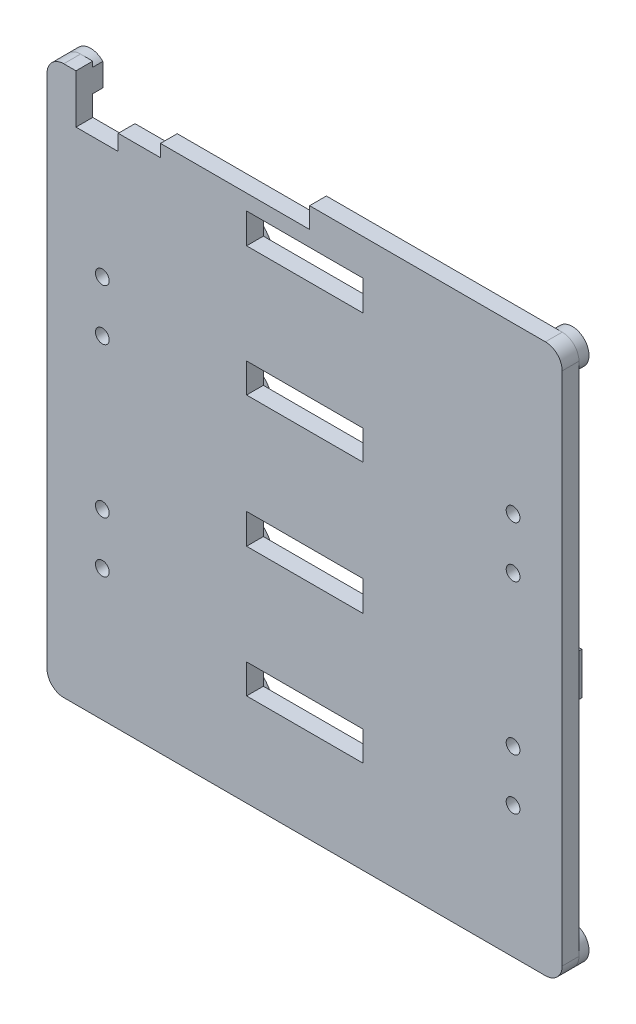
SolidWorks part; units mm, degrees
ref_plane "前视基准面" through (0, 0, 0) normal (0, 0, 1) x (1, 0, 0)
ref_plane "上视基准面" through (0, 0, 0) normal (0, 1, 0) x (1, 0, 0)
ref_plane "右视基准面" through (0, 0, 0) normal (1, 0, 0) x (0, 0, -1)
other "Configuration Table"
ref_plane "基准面1" through (0, 0, -42.5914) normal (0, 0, -1) x (-1, 0, 0)
sketch "草图1" plane through (0, 0, -42.5914) normal (0, 0, -1) x (-1, 0, 0)
  line L20 (41.4092, 120.2374) -> (-102.2385, 120.2373)
  line L21 (-107.2387, 115.2372) -> (-107.2386, -38.4842)
  line L22 (-102.2402, -43.4827) -> (41.4109, -43.4826)
  line L23 (46.4094, -38.4842) -> (46.4093, 115.2372)
  arc A20 (46.4093, 115.2372) -> (41.4092, 120.2374) centre (41.4092, 115.2372) ccw
  arc A21 (-102.2385, 120.2373) -> (-107.2387, 115.2372) centre (-102.2385, 115.2372) ccw
  arc A22 (-107.2386, -38.4842) -> (-102.2402, -43.4827) centre (-102.2402, -38.4842) ccw
  arc A23 (41.4109, -43.4826) -> (46.4094, -38.4842) centre (41.4109, -38.4842) ccw
extrude "凸台-拉伸1" add sketch "草图1" along normal blind 5
sketch "草图3" plane through (0, 0, -47.5914) normal (0, 0, -1) x (-1, 0, 0)
  line L5 (22.0323, 45.3277) -> (11.4184, 45.3277)
  line L6 (22.0323, 45.3277) -> (22.0323, 20.4419)
  line L7 (22.0323, 20.4419) -> (11.4184, 20.4419)
  line L8 (11.4184, 45.3277) -> (11.4184, 20.4419)
  line L9 (-66.1205, 38.2743) -> (-105.0787, 38.2743)
  line L10 (-66.1205, 38.2743) -> (-66.1205, 25.6801)
  line L11 (-66.1205, 25.6801) -> (-105.0787, 25.6801)
  line L12 (-105.0787, 38.2743) -> (-105.0787, 25.6801)
  line L13 (-76.2404, 116.5516) -> (-89.8192, 116.5516)
  line L14 (-76.2404, 116.5516) -> (-76.2404, 82.3988)
  line L15 (-76.2404, 82.3988) -> (-89.8192, 82.3988)
  line L16 (-89.8192, 116.5516) -> (-89.8192, 82.3988)
  line L17 (26.5757, 102.6562) -> (14.4763, 102.6562)
  line L18 (26.5757, 102.6562) -> (26.5757, 79.5664)
  line L19 (26.5757, 79.5664) -> (14.4763, 79.5664)
  line L20 (14.4763, 102.6562) -> (14.4763, 79.5664)
  line L21 (24.3318, -15.6667) -> (16.7254, -15.6667)
  line L22 (24.3318, -15.6667) -> (24.3318, -38.483)
  line L23 (24.3318, -38.483) -> (16.7254, -38.483)
  line L24 (16.7254, -15.6667) -> (16.7254, -38.483)
  line L25 (-76.2404, -15.6667) -> (-87.4137, -15.6667)
  line L26 (-76.2404, -15.6667) -> (-76.2404, -38.483)
  line L27 (-76.2404, -38.483) -> (-87.4137, -38.483)
  line L28 (-87.4137, -15.6667) -> (-87.4137, -38.483)
  circle A0 centre (-3.5966, 93.0119) radius 6.625 construction
  circle A1 centre (-3.581, 54.2036) radius 6.625 construction
  circle A2 centre (-59.0858, 90.0418) radius 6.625 construction
  circle A3 centre (-59.0702, 51.2335) radius 6.625 construction
  circle A4 centre (-59.039, -26.383) radius 6.625 construction
  circle A5 centre (-59.0546, 12.4253) radius 6.625 construction
  circle A6 centre (-3.5654, 15.3953) radius 6.625 construction
  circle A7 centre (-3.5498, -23.413) radius 6.625 construction
  circle A8 centre (-3.5966, 93.0119) radius 6.625 construction
  circle A9 centre (-3.581, 54.2036) radius 6.625 construction
  circle A10 centre (-59.0858, 90.0418) radius 6.625 construction
  circle A11 centre (-59.0702, 51.2335) radius 6.625 construction
  circle A12 centre (-59.039, -26.383) radius 6.625 construction
  circle A13 centre (-59.0546, 12.4253) radius 6.625 construction
  circle A14 centre (-3.5654, 15.3953) radius 6.625 construction
  circle A15 centre (-3.5498, -23.413) radius 6.625 construction
  circle A16 centre (41.4105, 115.237) radius 5
  circle A17 centre (41.4105, 115.237) radius 5
  circle A20 centre (-102.2375, 115.237) radius 2
  circle A21 centre (41.4105, 115.237) radius 2
  circle A22 centre (-102.2375, 115.237) radius 5
  circle A23 centre (-102.2375, 115.237) radius 5
  circle A24 centre (-102.2375, -38.483) radius 5
  circle A25 centre (-102.2375, -38.483) radius 5
  circle A26 centre (41.4105, -38.483) radius 5
  circle A27 centre (41.4105, -38.483) radius 5
  circle A28 centre (-3.5966, 93.0119) radius 9.625
  circle A29 centre (-3.581, 54.2036) radius 9.625
  circle A30 centre (-59.0858, 90.0418) radius 9.625
  circle A31 centre (-59.0702, 51.2335) radius 9.625
  circle A32 centre (-59.039, -26.383) radius 9.625
  circle A33 centre (-59.0546, 12.4253) radius 9.625
  circle A34 centre (-3.5654, 15.3953) radius 9.625
  circle A35 centre (-3.5498, -23.413) radius 9.625
  circle A36 centre (-102.2375, -38.483) radius 2
  circle A37 centre (41.4105, -38.483) radius 2
  dimension "D6" = 3
  dimension "D1" = 2.5
  dimension "D2" = 2.5
  dimension "D3" = 2.5
  dimension "D4" = 2.5
  dimension "D5" = 3
extrude "凸台-拉伸2" add sketch "草图3" along normal up to surface (3 mm away)
sketch "草图4" plane through (0, 0, -42.5914) normal (0, 0, 1) x (1, 0, 0)
  line L0 (-37.7635, 120.8202) -> (-37.7635, 105.691)
  line L1 (13.1152, 109.474) -> (47.8854, 109.474)
  line L2 (13.1152, 109.474) -> (13.1152, 100.474)
  line L3 (13.1152, 100.474) -> (47.8854, 100.474)
  line L4 (47.8854, 109.474) -> (47.8854, 100.474)
  line L5 (13.1152, 70.739) -> (47.8854, 70.739)
  line L6 (13.1152, 70.739) -> (13.1152, 61.939)
  line L7 (13.1152, 61.939) -> (47.8854, 61.939)
  line L8 (47.8854, 70.739) -> (47.8854, 61.939)
  line L9 (13.1152, 31.877) -> (47.8854, 31.877)
  line L10 (13.1152, 31.877) -> (13.1152, 22.877)
  line L11 (13.1152, 22.877) -> (47.8854, 22.877)
  line L12 (47.8854, 31.877) -> (47.8854, 22.877)
  line L13 (13.1152, -6.985) -> (47.8854, -6.985)
  line L14 (13.1152, -6.985) -> (13.1152, -15.785)
  line L15 (13.1152, -15.785) -> (47.8854, -15.785)
  line L16 (47.8854, -6.985) -> (47.8854, -15.785)
  line L18 (-37.7635, 105.691) -> (-25.1635, 105.691)
  line L19 (-25.1635, 105.691) -> (-25.1635, 110.396)
  line L20 (-25.1635, 110.396) -> (-12.5715, 110.396)
  line L21 (-12.5715, 110.396) -> (-12.5715, 114.0907)
  line L22 (-12.5715, 114.0907) -> (31.9075, 114.0907)
  line L23 (31.9075, 114.0907) -> (31.9075, 120.8202)
  line L24 (31.9075, 120.8202) -> (-37.7635, 120.8202)
  dimension "D1" = 1.5
  dimension "D2" = 1.5
  dimension "D3" = 1.5
  dimension "D4" = 1.5
  dimension "D5" = 1.5
  dimension "D6" = 1.5
  dimension "D7" = 1.5
  dimension "D8" = 1.5
  dimension "D9" = 1.5
  dimension "D10" = 1.5
  dimension "D11" = 1.5
  dimension "D12" = 1.5
  dimension "D13" = 1.5
  dimension "D14" = 1.5
  dimension "D15" = 1.5
  dimension "D16" = 1.5
  dimension "D17" = 1.5
extrude "切除-拉伸1" cut sketch "草图4" against normal through all
sketch "草图5" plane through (0, 0, -42.5914) normal (0, 0, 1) x (1, 0, 0)
  circle A0 centre (92.5906, -4.3106) radius 1.6 construction
  circle A1 centre (92.5906, 10.9394) radius 1.6 construction
  circle A2 centre (92.5907, 55.6894) radius 1.6 construction
  circle A3 centre (92.5907, 70.9394) radius 1.6 construction
  circle A4 centre (-29.9093, 55.6894) radius 1.6 construction
  circle A5 centre (-29.9094, -4.3106) radius 1.6 construction
  circle A6 centre (-29.9094, 10.9394) radius 1.6 construction
  circle A7 centre (-29.9093, 70.9394) radius 1.6 construction
  circle A8 centre (92.5906, -4.3106) radius 1.6 construction
  circle A9 centre (92.5906, 10.9394) radius 1.6 construction
  circle A10 centre (92.5907, 55.6894) radius 1.6 construction
  circle A11 centre (92.5907, 70.9394) radius 1.6 construction
  circle A12 centre (-29.9093, 55.6894) radius 1.6 construction
  circle A13 centre (-29.9094, -4.3106) radius 1.6 construction
  circle A14 centre (-29.9094, 10.9394) radius 1.6 construction
  circle A15 centre (-29.9093, 70.9394) radius 1.6 construction
  circle A16 centre (-29.9093, 70.9394) radius 2.05
  circle A17 centre (-29.9093, 55.6894) radius 2.05
  circle A18 centre (-29.9094, 10.9394) radius 2.05
  circle A19 centre (-29.9094, -4.3106) radius 2.05
  circle A20 centre (92.5906, -4.3106) radius 2.05
  circle A21 centre (92.5906, 10.9394) radius 2.05
  circle A22 centre (92.5907, 55.6894) radius 2.05
  circle A23 centre (92.5907, 70.9394) radius 2.05
  dimension "D1" = 4.1
extrude "切除-拉伸2" cut sketch "草图5" against normal blind 5
